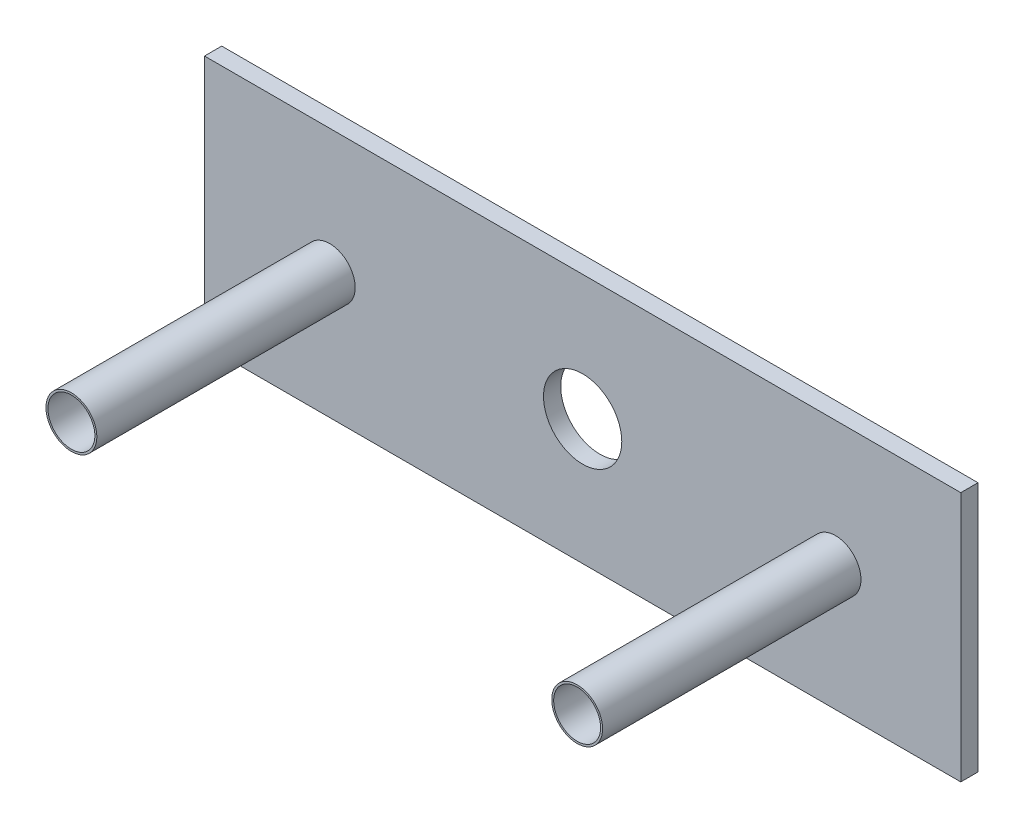
SolidWorks part; units mm, degrees
ref_plane "Plan de face" through (0, 0, 0) normal (0, 0, 1) x (1, 0, 0)
ref_plane "Plan de dessus" through (0, 0, 0) normal (0, 1, 0) x (1, 0, 0)
ref_plane "Plan de droite" through (0, 0, 0) normal (1, 0, 0) x (0, 0, -1)
sketch "Esquisse1" plane through (0, 0, 0) normal (0, 0, 1) x (1, 0, 0)
  line L1 (-47.6288, 18.2599) -> (48.9712, 18.2599)
  line L2 (-47.6288, 18.2599) -> (-47.6288, -13.7401)
  line L3 (-47.6288, -13.7401) -> (48.9712, -13.7401)
  line L4 (48.9712, 18.2599) -> (48.9712, -13.7401)
  dimension "D1" = 96.6
  dimension "D2" = 32
extrude "Boss.-Extru.1" add sketch "Esquisse1" along normal blind 2.2
sketch "Esquisse6" plane through (0, 0, 2.2) normal (0, 0, 1) x (1, 0, 0)
  line L0 (-47.6288, 18.2599) -> (-47.6288, -13.7401) construction
  line L3 (48.9712, 18.2599) -> (-47.6288, 18.2599) construction
  line L4 (48.9712, -13.7401) -> (48.9712, 18.2599) construction
  circle A0 centre (-31.6288, 2.2599) radius 3.25
  circle A1 centre (32.9712, 2.2599) radius 3.25
  dimension "D1" = 6.5
  dimension "D4" = 6.5
  dimension "D2" = 16
  dimension "D3" = 16
  dimension "D5" = 16
  dimension "D6" = 16
extrude "Boss.-Extru.2" add sketch "Esquisse6" along normal blind 33
sketch "Esquisse7" plane through (0, 0, 35.2) normal (0, 0, 1) x (1, 0, 0)
  line L1 (-47.6288, 18.2599) -> (-47.6288, -13.7401) construction
  line L3 (48.9712, 18.2599) -> (-47.6288, 18.2599) construction
  line L4 (48.9712, -13.7401) -> (48.9712, 18.2599) construction
  line L5 (-47.6288, -13.7401) -> (48.9712, -13.7401) construction
  circle A0 centre (-31.6288, 2.2599) radius 3
  circle A1 centre (32.9712, 2.2599) radius 3
  circle A2 centre (0.6712, 2.2599) radius 5
  dimension "D1" = 6
  dimension "D4" = 6
  dimension "D7" = 10
  dimension "D2" = 16
  dimension "D3" = 16
  dimension "D5" = 16
  dimension "D6" = 16
  dimension "D8" = 16
  dimension "D9" = 48.3
extrude "Enlèv. mat.-Extru.1" cut sketch "Esquisse7" against normal through all
